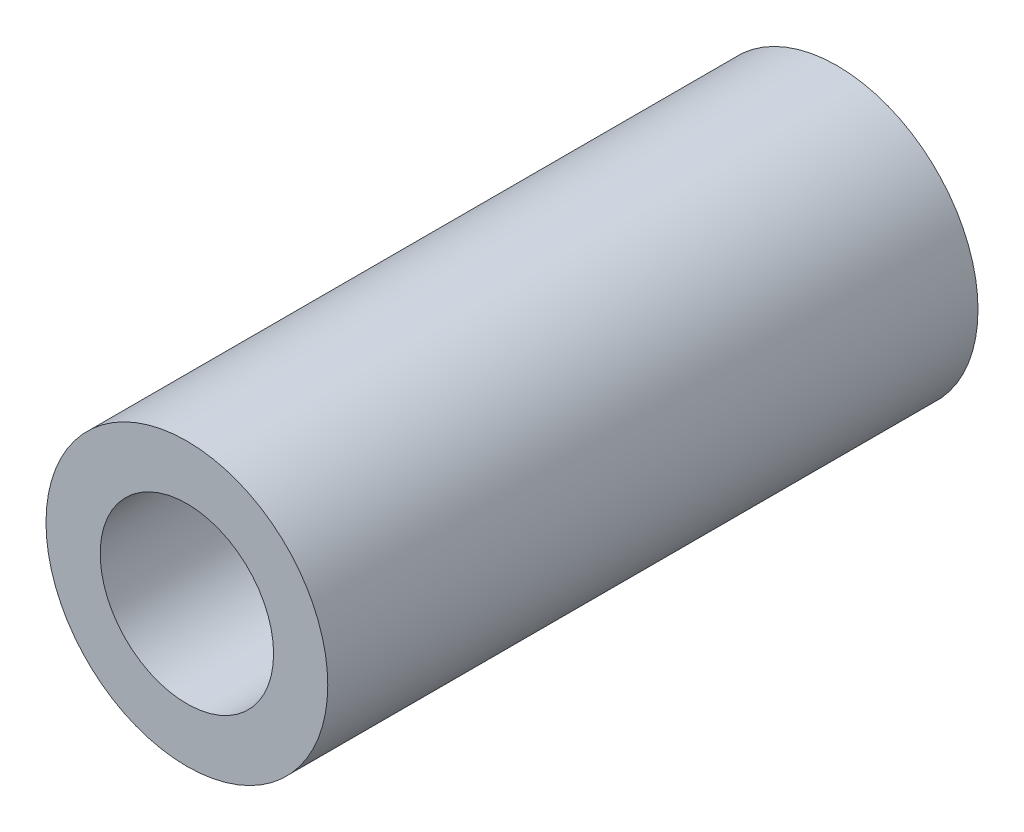
SolidWorks part; units mm, degrees
ref_plane "Front Plane" through (0, 0, 0) normal (0, 0, 1) x (1, 0, 0)
ref_plane "Top Plane" through (0, 0, 0) normal (0, 1, 0) x (1, 0, 0)
ref_plane "Right Plane" through (0, 0, 0) normal (1, 0, 0) x (0, 0, -1)
sketch "Sketch1" plane through (0, 0, 0) normal (0, 0, 1) x (1, 0, 0)
  circle A0 centre (0, 0) radius 1.6
  circle A1 centre (0, 0) radius 2.6
  dimension "D1" = 3.2
  dimension "D2" = 1
extrude "Boss-Extrude1" add sketch "Sketch1" along normal blind 12
